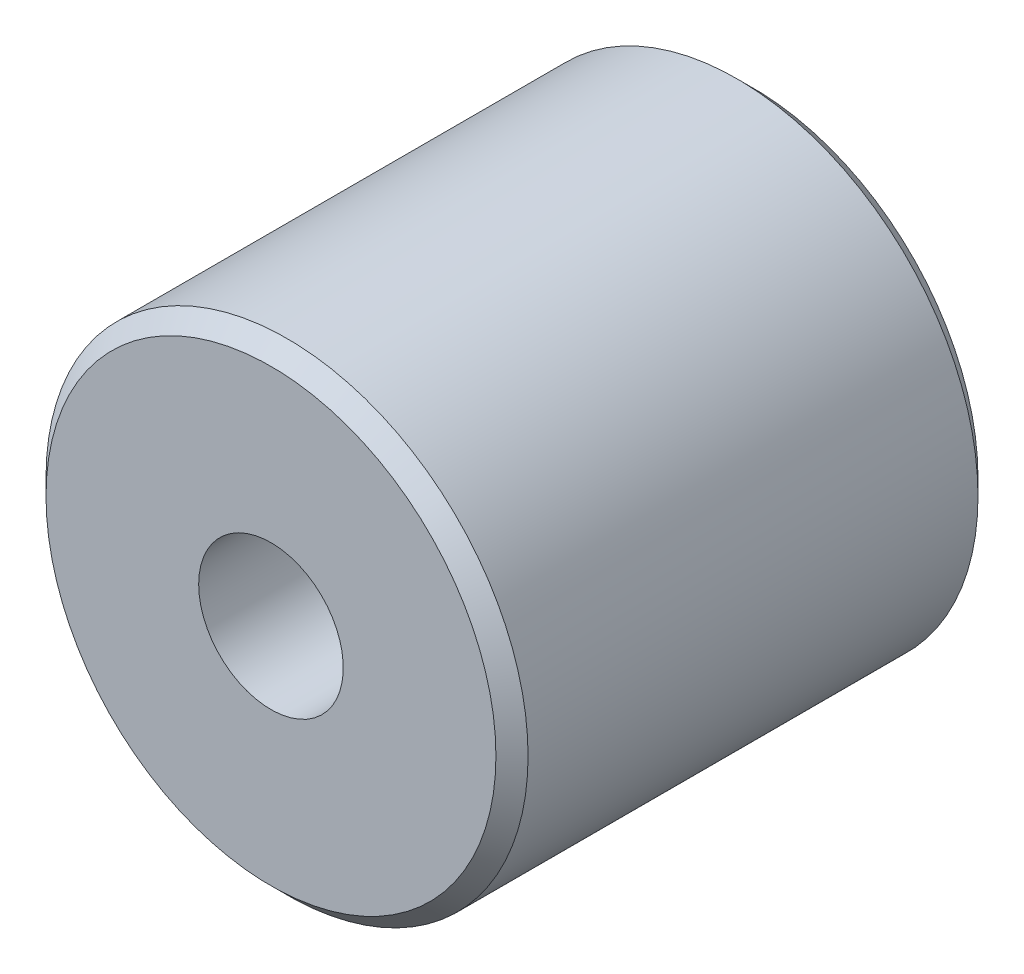
SolidWorks part; units mm, degrees
ref_plane "前基準面" through (0, 0, 0) normal (0, 0, 1) x (1, 0, 0)
ref_plane "上基準面" through (0, 0, 0) normal (0, 1, 0) x (1, 0, 0)
ref_plane "右基準面" through (0, 0, 0) normal (1, 0, 0) x (0, 0, -1)
sketch "草圖1" plane through (0, 0, 0) normal (1, 0, 0) x (0, 0, -1)
  line L0 (-2.8315, 0) -> (34.4213, 0) construction
  line L3 (0, 0) -> (0, 15)
  line L4 (0, 15) -> (30, 15)
  line L5 (30, 15) -> (30, 0)
  line L6 (30, 0) -> (0, 0)
  dimension "D2" = 30
  dimension "D4" = 30
revolve "旋轉1" add sketch "草圖1" angle 360 about L0
hole_wizard "M8 六角承窩頭蓋螺釘的柱孔1" positions "草圖3" profile "草圖2" counterbore size "M8" standard "ISO" end condition through all
sketch "草圖3" plane through (0, 0, -30) normal (0, 0, -1) x (-1, 0, 0)
  circle A2 centre (0, 0) radius 15 construction
  point P0 (0, 0)
sketch "草圖2" plane through (0, 0, -30) normal (1, 0, 0) x (0, 1, 0)
  line L0 (0, 0) -> (0, 30)
  line L1 (0, 30) -> (4.5, 30)
  line L3 (4.5, 30) -> (4.5, 8)
  line L4 (4.5, 8) -> (7.5, 8)
  line L5 (7.5, 8) -> (7.5, 0)
  line L7 (7.5, 0) -> (0, 0)
  line L11 (0, -6.35) -> (0, 107.95) construction
  dimension "貫穿孔直徑" = 9
  dimension "貫穿孔深度" = 30
  dimension "柱孔直徑" = 15
  dimension "柱孔深度" = 8
chamfer "導角1" distance 1 angle 45 2 edges at (15, 0, -30) (15, 0, 0)
